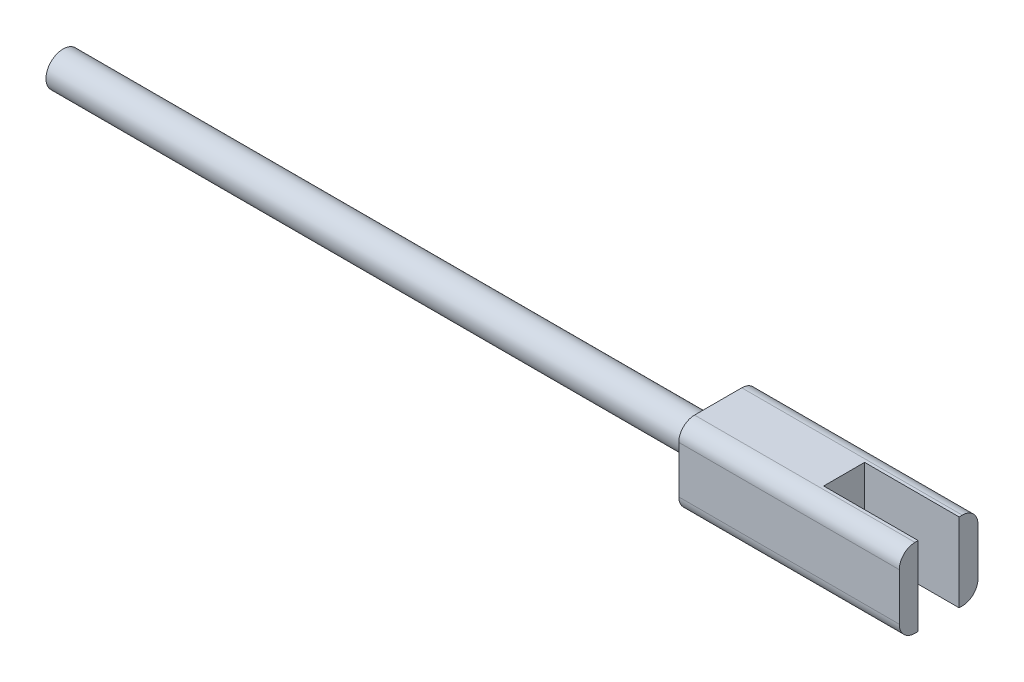
SolidWorks part; units mm, degrees
ref_plane "Front Plane" through (0, 0, 0) normal (0, 0, 1) x (1, 0, 0)
ref_plane "Top Plane" through (0, 0, 0) normal (0, 1, 0) x (1, 0, 0)
ref_plane "Right Plane" through (0, 0, 0) normal (1, 0, 0) x (0, 0, -1)
sketch "Sketch1" plane through (0, 0, 0) normal (1, 0, 0) x (0, 0, -1)
  circle A0 centre (0, 0) radius 1.09
extrude "Boss-Extrude1" add sketch "Sketch1" along normal blind 43.594
ref_plane "Plane1" through (41.594, 0, 0) normal (1, 0, 0) x (0, 0, -1)
sketch "Sketch2" plane through (41.594, 0, 0) normal (1, 0, 0) x (0, 0, -1)
  line L0 (-1.5, -2.5) -> (1.5, -2.5)
  line L1 (2.5, -1.5) -> (2.5, 1.5)
  line L2 (1.5, 2.5) -> (-1.5, 2.5)
  line L3 (-2.5, 1.5) -> (-2.5, -1.5)
  arc A0 (1.5, -2.5) -> (2.5, -1.5) centre (1.5, -1.5) ccw
  arc A1 (2.5, 1.5) -> (1.5, 2.5) centre (1.5, 1.5) ccw
  arc A2 (-1.5, 2.5) -> (-2.5, 1.5) centre (-1.5, 1.5) ccw
  arc A3 (-2.5, -1.5) -> (-1.5, -2.5) centre (-1.5, -1.5) ccw
extrude "Boss-Extrude2" add sketch "Sketch2" along normal blind 14
sketch "Sketch3" plane through (0, 0, 0) normal (0, 1, 0) x (1, 0, 0)
  line L0 (49.594, 1.3) -> (56.594, 1.3)
  line L1 (56.594, 1.3) -> (56.594, -1.3)
  line L2 (56.594, -1.3) -> (49.594, -1.3)
  line L3 (49.594, -1.3) -> (49.594, 1.3)
extrude "Cut-Extrude1" cut sketch "Sketch3" against normal through all and the other way through all
